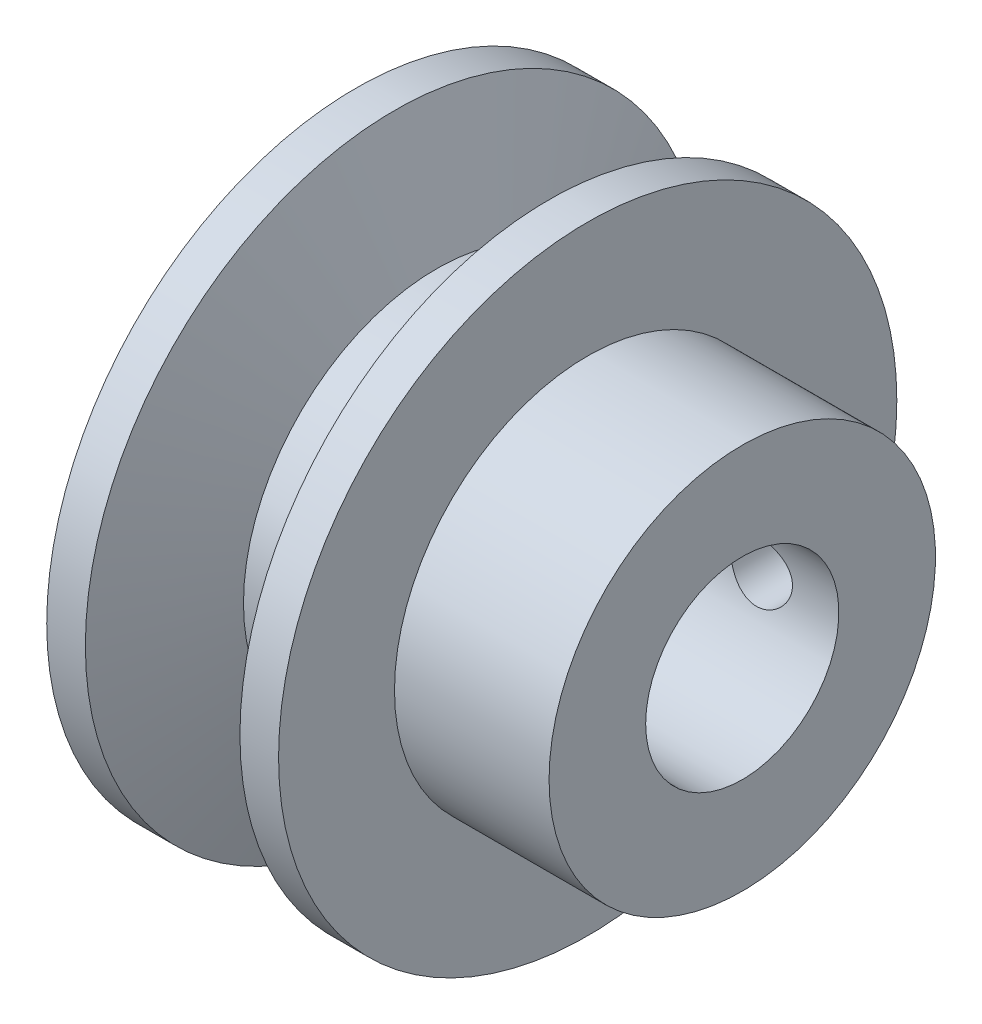
SolidWorks part; units mm, degrees
ref_plane "Front Plane" through (0, 0, 0) normal (0, 0, 1) x (1, 0, 0)
ref_plane "Top Plane" through (0, 0, 0) normal (0, 1, 0) x (1, 0, 0)
ref_plane "Right Plane" through (0, 0, 0) normal (1, 0, 0) x (0, 0, -1)
sketch "Sketch1" plane through (0, 0, 0) normal (0, 1, 0) x (1, 0, 0)
  line L0 (-23.2215, 0) -> (75.3791, 0) construction
  line L1 (0, 40) -> (0, 20)
  line L2 (0, 40) -> (5, 40)
  line L3 (25, 40) -> (30, 40)
  line L4 (10.4596, 25) -> (19.5404, 25)
  line L5 (5, 40) -> (10.4596, 25)
  line L6 (25, 40) -> (19.5404, 25)
  line L7 (30, 40) -> (30, 25)
  line L8 (30, 25) -> (36, 25)
  line L9 (50, 25) -> (50, 12.5)
  line L10 (5, 12.5) -> (36, 12.5)
  line L11 (40, 35.3215) -> (40, 3.3433) construction
  line L12 (36, 25) -> (36, 12.5)
  line L13 (44, 25) -> (44, 12.5)
  line L14 (44, 25) -> (50, 25)
  line L15 (5, 12.5) -> (0, 20)
  line L16 (44, 12.5) -> (50, 12.5)
  line L17 (36, 25) -> (44, 25)
  line L18 (36, 12.5) -> (44, 12.5)
  dimension "D1" = 5
  dimension "D2" = 5
  dimension "D3" = 40
  dimension "D4" = 20
  dimension "D5" = 25
  dimension "D7" = 20
  dimension "D8" = 12.5
  dimension "D9" = 10
  dimension "D10" = 4
revolve "Revolve1" add sketch "Sketch1" angle 360 about L0
sketch "Sketch7" plane through (0, 0, 0) normal (0, 1, 0) x (1, 0, 0)
  line L0 (40, 25) -> (40, 12.5) construction
  line L1 (50, 25) -> (30, 25) construction
  line L2 (50, -25) -> (50, 25) construction
  line L3 (36, 25) -> (36, 12.5)
  dimension "D1" = 10
  dimension "D2" = 12.5
  dimension "D4" = 4
revolve "Revolve-Thin2" add sketch "Sketch7" angle 360 mid plane about L0
sketch "Sketch8" plane through (0, 0, -25) normal (0, 0, -1) x (-1, 0, 0)
  circle A0 centre (-40, 0) radius 4
extrude "Cut-Extrude1" cut sketch "Sketch8" against normal up to next
sketch "Sketch9" plane through (0, 0, -12.5) normal (0, 0, 1) x (1, 0, 0)
  line L0 (50, 9.798) -> (50, -9.798)
  arc A0 (50, -9.798) -> (50, 9.798) centre (40, 0) ccw
extrude "Cut-Extrude2" cut sketch "Sketch9" against normal up to next
sketch "Sketch12" plane through (50, 0, 0) normal (1, 0, 0) x (0, 0, -1)
  line L0 (25, 14) -> (25, -14)
  line L1 (25, -14) -> (20.7123, -14)
  line L2 (25, 14) -> (20.7123, 14)
  arc A0 (20.7123, -14) -> (20.7123, 14) centre (0, 0) ccw
  arc M2 (23, 9.798) -> (23, -9.798) centre (0, 0) ccw
  line M3 (23, -9.798) -> (25, -9.798)
  line M4 (25, -9.798) -> (25, 9.798)
  line M5 (25, 9.798) -> (23, 9.798)
extrude "Cut-Extrude3" cut sketch "Sketch12" against normal blind 20 contours L0 L2 M2 M5 | A0 L0 M5 | L1 L0 M3 M2 | A0 M3 M4
